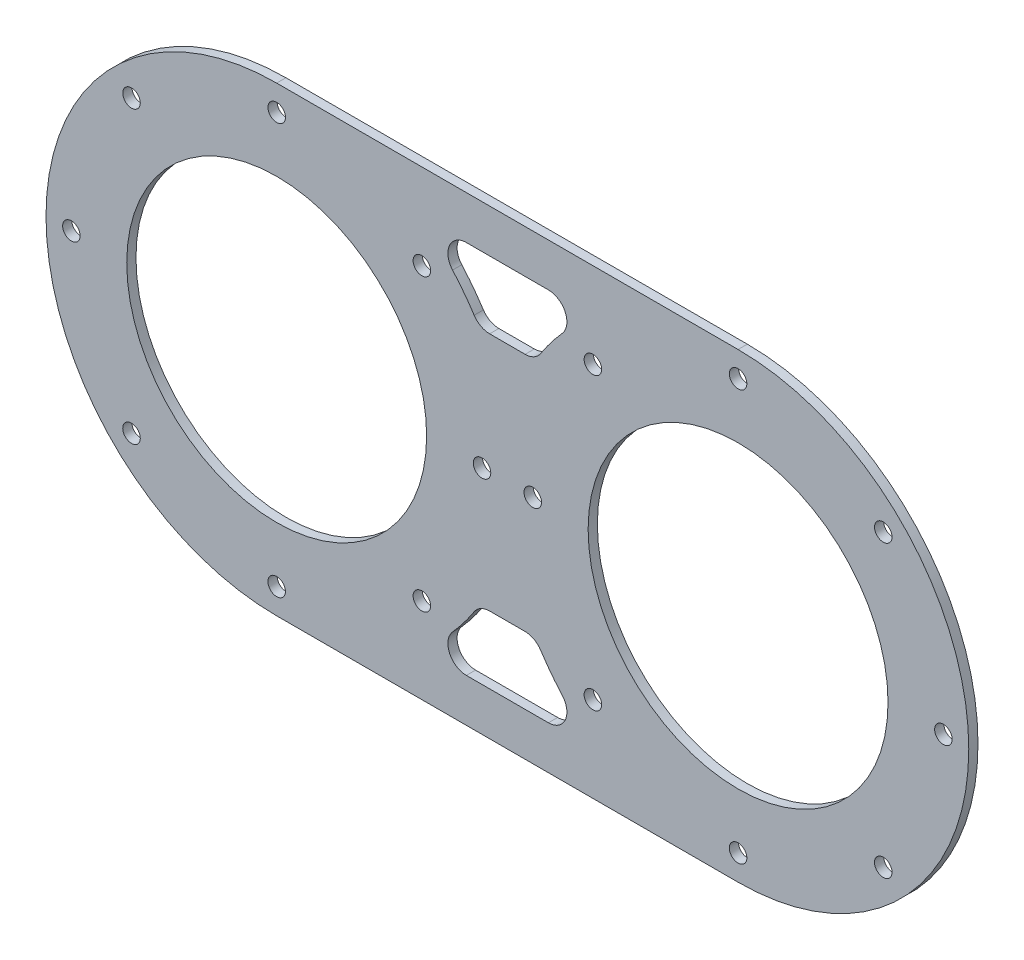
SolidWorks part; units mm, degrees
ref_plane "前视基准面" through (0, 0, 0) normal (0, 0, 1) x (1, 0, 0)
ref_plane "上视基准面" through (0, 0, 0) normal (0, 1, 0) x (1, 0, 0)
ref_plane "右视基准面" through (0, 0, 0) normal (1, 0, 0) x (0, 0, -1)
sketch "草图1" plane through (0, 0, 0) normal (0, 0, 1) x (1, 0, 0)
  line L5 (55, 0) -> (-55, 0) construction
  line L9 (-6.0713, -26.0152) -> (6.0713, -26.0152)
  line L11 (-50, 50) -> (-25, 50)
  line L12 (19.0773, 40.624) -> (-19.0773, 40.624)
  line L13 (-6.0713, 26.0152) -> (6.0713, 26.0152)
  line L14 (19.0773, -40.624) -> (-19.0773, -40.624)
  line L17 (-50, -50) -> (-25, -50)
  line L18 (0, -55) -> (0, 55) construction
  line L19 (50, -50) -> (25, -50)
  line L22 (50, 50) -> (25, 50)
  line L23 (-25, -50) -> (25, -50)
  line L24 (-25, 50) -> (25, 50)
  arc A2 (50, 50) -> (50, -50) centre (50, 0) cw
  arc A3 (-50, 50) -> (-50, -50) centre (-50, 0) ccw
  circle A4 centre (-50, 0) radius 32.5
  circle A5 centre (50, 0) radius 32.5
  arc A12 (-19.0773, 40.624) -> (-6.0713, 26.0152) centre (-50, 0) cw
  arc A13 (-19.0773, -40.624) -> (-6.0713, -26.0152) centre (-50, 0) ccw
  arc A14 (19.0773, -40.624) -> (6.0713, -26.0152) centre (50, 0) cw
  arc A15 (19.0773, 40.624) -> (6.0713, 26.0152) centre (50, 0) ccw
  point P11 (50, 0)
  point P14 (5.4301, 21.5271)
  point P18 (18.3449, 41.5862)
  point P27 (6.0713, 26.0152)
  point P29 (0, -45)
  point P30 (0, -40.624)
  point P31 (0, -26.0152)
  point P32 (0, 26.0152)
  point P33 (0, 40.624)
  point P34 (0, 45)
  dimension "D1" = 50
  dimension "D2" = 100
  dimension "D3" = 65
  dimension "D4" = 65
extrude "凸台-拉伸1" add sketch "草图1" along normal blind 2
fillet "圆角1" radius 4 8 edges at (6.0713, 26.0152, 1) (-6.0713, 26.0152, 1) (19.0773, 40.624, 1) (-19.0773, 40.624, 1) (-6.0713, -26.0152, 1) (6.0713, -26.0152, 1) (19.0773, -40.624, 1) (-19.0773, -40.624, 1)
sketch "草图2" plane through (0, 0, 2) normal (0, 0, 1) x (1, 0, 0)
  line L0 (0, 0) -> (0, 13.835) construction
  circle A16 centre (50, 0) radius 44.5 construction
  circle A17 centre (94.5, 0) radius 1.9
  circle A18 centre (81.4663, -31.4663) radius 1.9
  circle A19 centre (50, -44.5) radius 1.9
  circle A20 centre (18.5337, -31.4663) radius 1.9
  circle A21 centre (5.5, 0) radius 1.9
  circle A22 centre (18.5337, 31.4663) radius 1.9
  circle A23 centre (50, 44.5) radius 1.9
  circle A24 centre (81.4663, 31.4663) radius 1.9
  circle A25 centre (-50, 0) radius 44.5 construction
  circle A26 centre (-81.4663, 31.4663) radius 1.9
  circle A27 centre (-50, 44.5) radius 1.9
  circle A28 centre (-18.5337, 31.4663) radius 1.9
  circle A29 centre (-5.5, 0) radius 1.9
  circle A30 centre (-18.5337, -31.4663) radius 1.9
  circle A31 centre (-50, -44.5) radius 1.9
  circle A32 centre (-81.4663, -31.4663) radius 1.9
  circle A33 centre (-94.5, 0) radius 1.9
  point P22 (50, 0)
  point P47 (-50, 0)
  dimension "D1" = 3.8
  dimension "D2" = 8
extrude "切除-拉伸1" cut sketch "草图2" against normal blind 10
